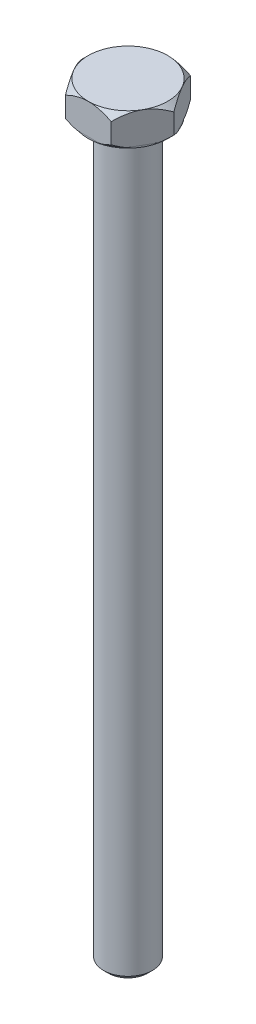
SolidWorks part; units mm, degrees
material "Cast Stainless Steel"
ref_plane "Front Plane" through (0, 0, 0) normal (0, 0, 1) x (1, 0, 0)
ref_plane "Top Plane" through (0, 0, 0) normal (0, 1, 0) x (1, 0, 0)
ref_plane "Right Plane" through (0, 0, 0) normal (1, 0, 0) x (0, 0, -1)
sketch "Sketch1" plane through (0, 0, 0) normal (0, 1, 0) x (1, 0, 0)
  line L0 (0, 0) -> (7.5056, 0) construction
  line L1 (7.5056, 0) -> (3.7528, 6.5)
  line L2 (3.7528, 6.5) -> (-3.7528, 6.5)
  line L3 (-3.7528, 6.5) -> (-7.5056, 0)
  line L4 (-7.5056, 0) -> (-3.7528, -6.5)
  line L5 (-3.7528, -6.5) -> (3.7528, -6.5)
  line L6 (3.7528, -6.5) -> (7.5056, 0)
  circle A0 centre (0, 0) radius 6.5 construction
  dimension "D1" = 13
extrude "Boss-Extrude1" add sketch "Sketch1" against normal blind 5.3
sketch "Sketch4" plane through (0, 0, 0) normal (1, 0, 0) x (0, 0, -1)
  line L0 (-6.5, 0) -> (-8.15, 0)
  line L1 (-8.15, 0) -> (-8.15, -1.65)
  line L2 (-8.15, -1.65) -> (-6.5, 0)
  line L3 (-6.5, -2.65) -> (6.5, -2.65) construction
  line L4 (-8.15, -3.65) -> (-6.5, -5.3)
  line L5 (-8.15, -5.3) -> (-8.15, -3.65)
  line L6 (-6.5, -5.3) -> (-8.15, -5.3)
  line L7 (0, 0) -> (0, -2.65) construction
  dimension "D1" = 45
  dimension "D2" = 2.65
  dimension "D3" = 1.65
  dimension "D4" = 13
revolve "Cut-Revolve1" cut sketch "Sketch4" angle 360 about L7
sketch "Sketch2" plane through (0, -5.3, 0) normal (0, -1, 0) x (1, 0, 0)
  circle A0 centre (0, 0) radius 6.5
  dimension "D1" = 13
extrude "Cut-Extrude1" cut sketch "Sketch2" against normal blind 0.265 flip side to cut
sketch "Sketch3" plane through (0, -5.3, 0) normal (0, -1, 0) x (1, 0, 0)
  circle A0 centre (0, 0) radius 4
  dimension "D1" = 8
extrude "Boss-Extrude2" add sketch "Sketch3" along normal blind 120
chamfer "Chamfer1" distance 0.8 angle 45 1 edges at (0, -125.3, -4)
equation "\"k\"= 5.3"
equation "\"e\"= 14.38"
equation "\"S\"= 13"
equation "\"L\"= 120"
equation "\"D1@Sketch1\"=\"S\""
equation "\"D1@Boss-Extrude1\"=\"k\""
equation "\"D1@Sketch2\"=\"S\""
equation "\"D1@Cut-Extrude1\"=\"k\"/20"
equation "\"d\"= 8"
equation "\"D1@Sketch3\"=\"d\""
equation "\"D1@Boss-Extrude2\"=\"L\""
equation "\"D2@Sketch4\"=\"k\"/2"
equation "\"D3@Sketch4\"=\"D2@Sketch4\"-1"
equation "\"D4@Sketch4\"=\"S\""
equation "\"D1@Chamfer1\"=\"d\"/10"
